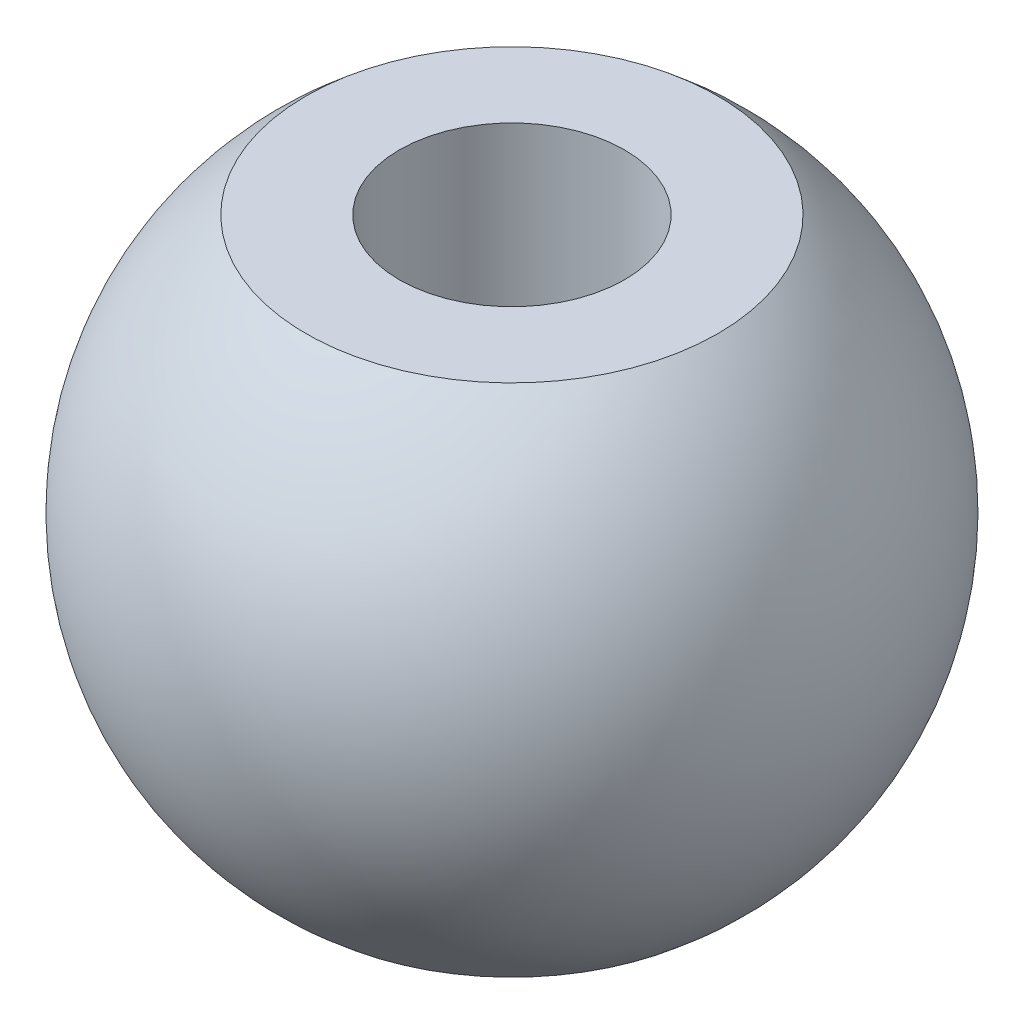
SolidWorks part; units mm, degrees
ref_plane "Front Plane" through (0, 0, 0) normal (0, 0, 1) x (1, 0, 0)
ref_plane "Top Plane" through (0, 0, 0) normal (0, 1, 0) x (1, 0, 0)
ref_plane "Right Plane" through (0, 0, 0) normal (1, 0, 0) x (0, 0, -1)
sketch "Sketch1" plane through (0, 0, 0) normal (0, 0, 1) x (1, 0, 0)
  line L8 (0, 4) -> (0, -4)
  line L9 (0, -4) -> (-3.2, -4)
  line L10 (0, 4) -> (-3.2, 4)
  arc A1 (-3.2, 4) -> (-3.2, -4) centre (0, 0) ccw
  dimension "D3" = 8
  dimension "D1" = 3.2
  dimension "D2" = 3.2
revolve "Revolve2" add sketch "Sketch1" angle 360 about L8
sketch "Sketch2" plane through (0, 4, 0) normal (0, 1, 0) x (1, 0, 0)
  circle A0 centre (0, 0) radius 1.75
  dimension "D1" = 3.5
extrude "Cut-Extrude1" cut sketch "Sketch2" against normal through all
